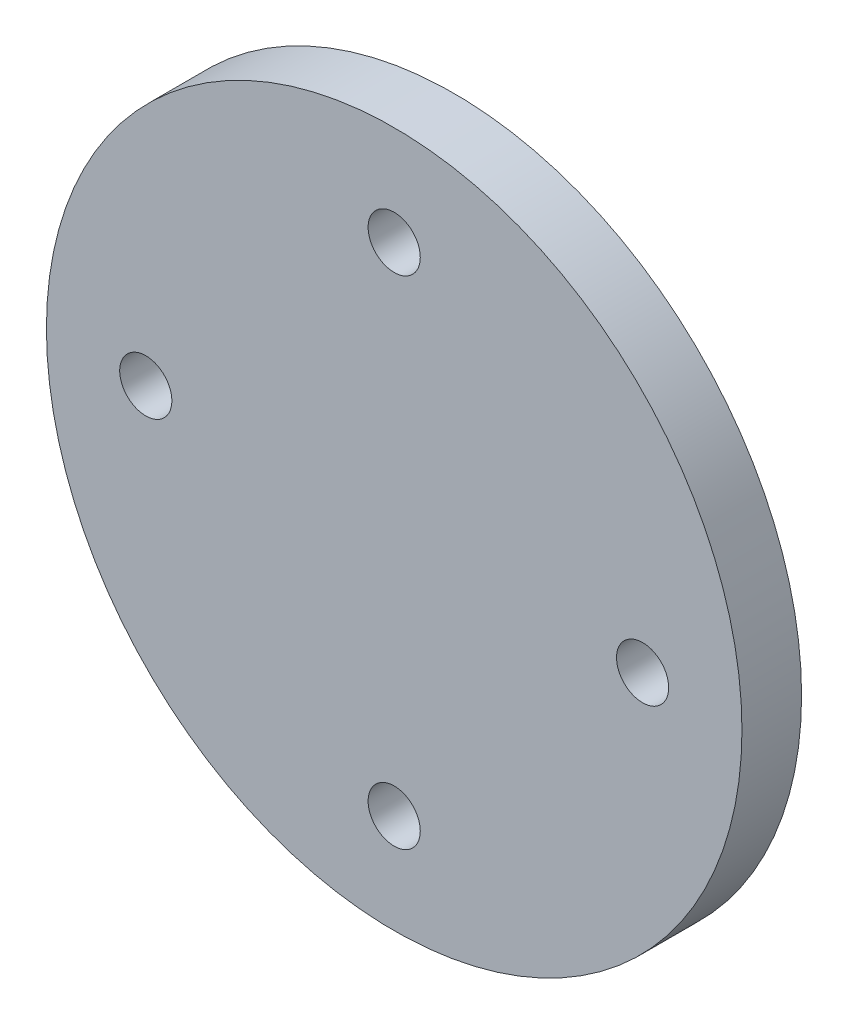
SolidWorks part; units mm, degrees
ref_plane "Alzado" through (0, 0, 0) normal (0, 0, 1) x (1, 0, 0)
ref_plane "Planta" through (0, 0, 0) normal (0, 1, 0) x (1, 0, 0)
ref_plane "Vista lateral" through (0, 0, 0) normal (1, 0, 0) x (0, 0, -1)
sketch "Sketch1" plane through (0, 0, 0) normal (0, 0, 1) x (1, 0, 0)
  circle A0 centre (0, 0) radius 70
  dimension "D1" = 140
extrude "Boss-Extrude1" add sketch "Sketch1" along normal blind 12
hole_wizard "Tap Drill for M12x1.5 Tap1" positions "3DSketch1" profile "Sketch2" hole size "M12x1.5" standard "ISO" end condition through all
sketch3d "3DSketch1"
  point P0 (0, 50, 12)
  dimension "D1" = 50
  dimension "D2" = 0
sketch "Sketch2" plane through (0, 50, 12) normal (1, 0, 0) x (0, -1, 0)
  line L0 (0, 0) -> (0, 12)
  line L1 (0, 12) -> (5.25, 12)
  line L2 (5.25, 12) -> (5.25, 0)
  line L5 (5.25, 0) -> (0, 0)
  line L11 (0, -6.35) -> (0, 107.95) construction
  dimension "Thru Hole Dia." = 10.5
  dimension "Thru Hole Depth" = 12
pattern_circular "CirPattern1" count 4 every 90 about axis through (0, 0, 0) along (0, 0, 1) of "Tap Drill for M12x1.5 Tap1"
